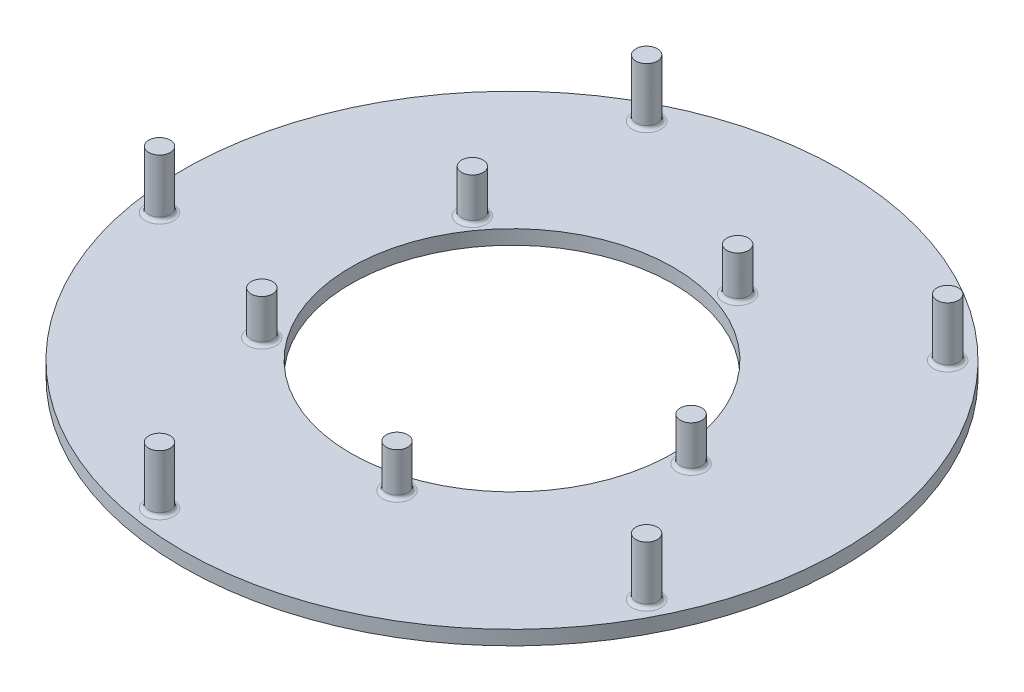
SolidWorks part; units mm, degrees
ref_plane "Front Plane" through (0, 0, 0) normal (0, 0, 1) x (1, 0, 0)
ref_plane "Top Plane" through (0, 0, 0) normal (0, 1, 0) x (1, 0, 0)
ref_plane "Right Plane" through (0, 0, 0) normal (1, 0, 0) x (0, 0, -1)
sketch "Sketch1" plane through (0, 0, 0) normal (0, 1, 0) x (1, 0, 0)
  circle A0 centre (0, 0) radius 22.5
  circle A1 centre (0, 0) radius 46
  dimension "D1" = 45
  dimension "D2" = 92
extrude "Boss-Extrude1" add sketch "Sketch1" along normal blind 2
sketch "Sketch2" plane through (0, 2, 0) normal (0, 1, 0) x (1, 0, 0)
  line L0 (-67.5192, 0) -> (70.5599, 0) construction
  line L1 (0, 58.8306) -> (0, -59.2797) construction
  line L2 (0, 0) -> (30.4056, 30.4056) construction
  circle A0 centre (25, 0) radius 1.5
  circle A1 centre (30.4056, 30.4056) radius 1.5
  circle A2 centre (0, 0) radius 25 construction
  circle A3 centre (0, 0) radius 43 construction
  dimension "D1" = 3
  dimension "D2" = 3
  dimension "D3" = 50
  dimension "D4" = 86
  dimension "D5" = 45
extrude "Boss-Extrude2" add sketch "Sketch2" along normal blind 6
fillet "Fillet1" radius 0.5 2 edges at (30.4056, 2, -28.9056) (25, 2, 1.5)
sketch "Sketch3" plane through (0, 8, 0) normal (0, 1, 0) x (1, 0, 0)
  circle A0 centre (30.4056, 30.4056) radius 1.5 construction
  circle A1 centre (30.4056, 30.4056) radius 1.5
extrude "Boss-Extrude3" add sketch "Sketch3" along normal blind 2
pattern_circular "CirPattern1" count 5 over 360 about axis through (0, 0, 0) along (0, 1, 0) of "Boss-Extrude2", "Fillet1", "Boss-Extrude3"
